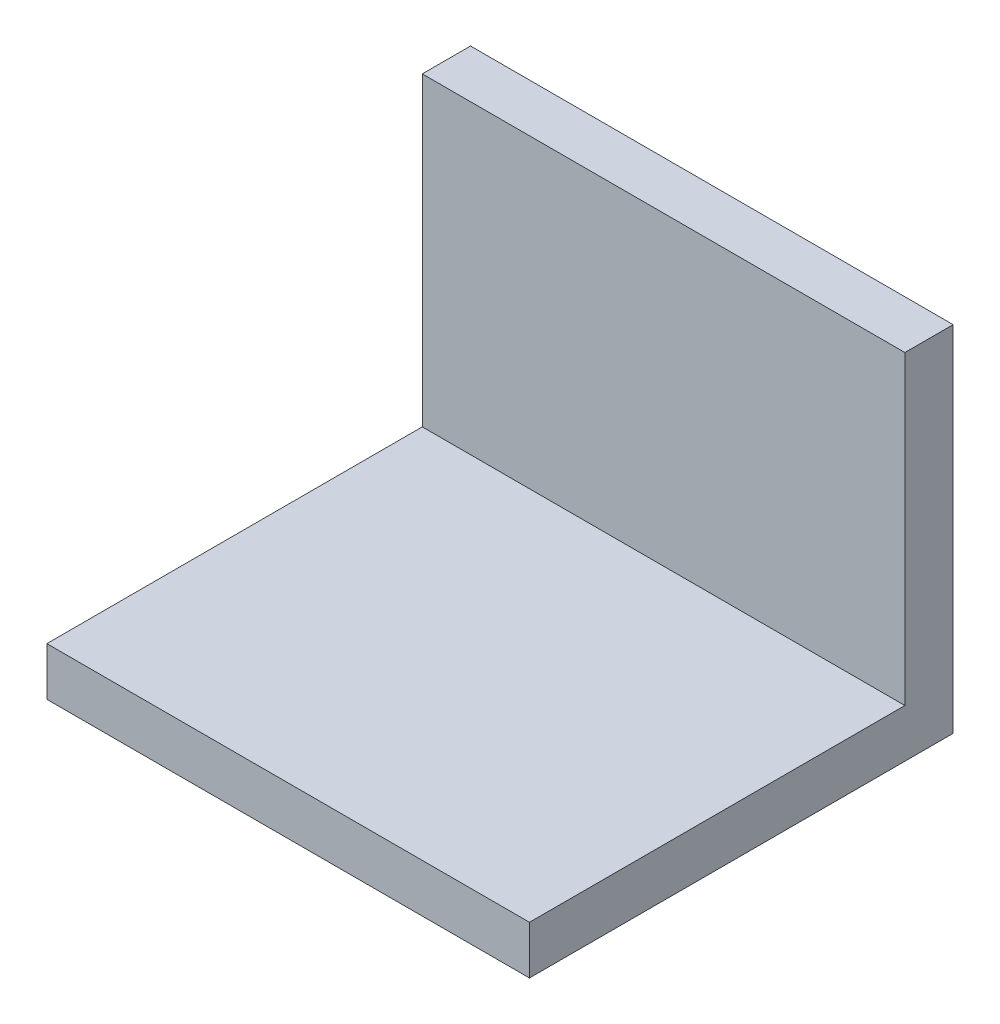
SolidWorks part; units mm, degrees
ref_plane "Front Plane" through (0, 0, 0) normal (0, 0, 1) x (1, 0, 0)
ref_plane "Top Plane" through (0, 0, 0) normal (0, 1, 0) x (1, 0, 0)
ref_plane "Right Plane" through (0, 0, 0) normal (1, 0, 0) x (0, 0, -1)
sketch "Sketch1" plane through (0, 0, 0) normal (1, 0, 0) x (0, 0, -1)
  line L0 (0, 0) -> (66.894, 0)
  line L1 (66.894, 0) -> (66.894, 55.8859)
  line L2 (66.894, 55.8859) -> (59.274, 55.8859)
  line L3 (59.274, 55.8859) -> (59.274, 7.62)
  line L4 (59.274, 7.62) -> (0, 7.62)
  line L5 (0, 7.62) -> (0, 0)
extrude "Extrude1" add sketch "Sketch1" against normal blind 76.2
